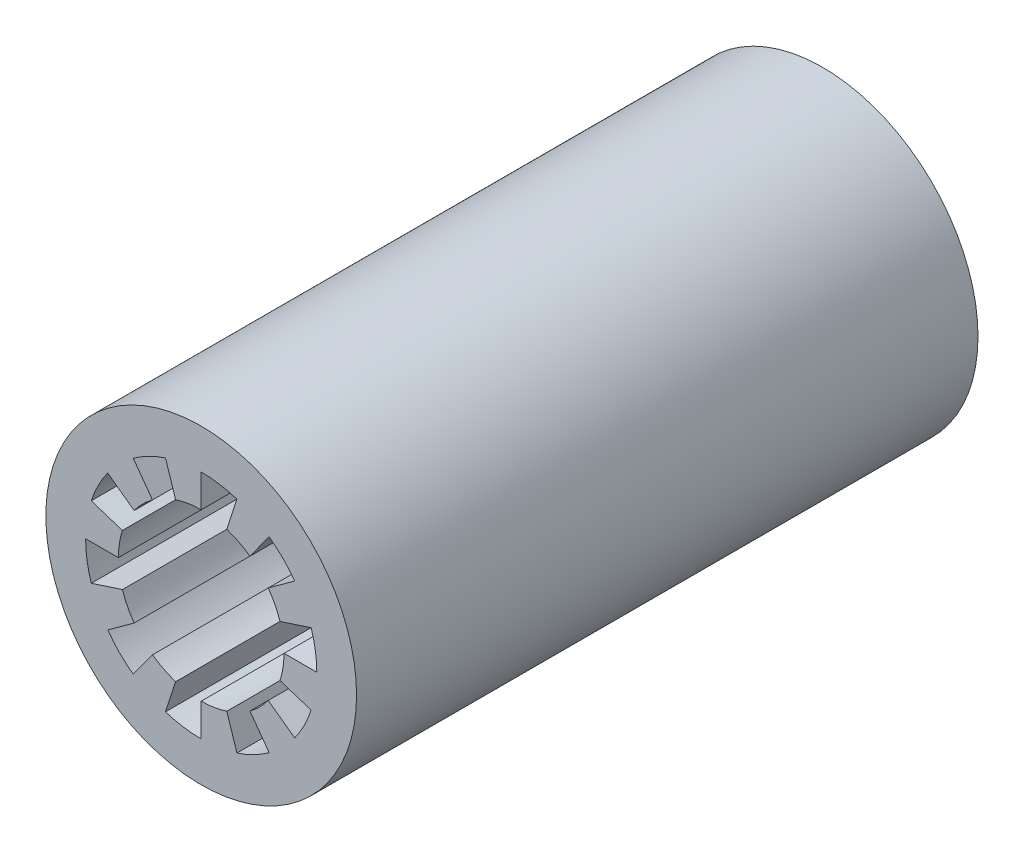
SolidWorks part; units mm, degrees
ref_plane "Front" through (0, 0, 0) normal (0, 0, 1) x (1, 0, 0)
ref_plane "Top" through (0, 0, 0) normal (0, 1, 0) x (1, 0, 0)
ref_plane "Right" through (0, 0, 0) normal (1, 0, 0) x (0, 0, -1)
sketch "Эскиз1" plane through (0, 0, 0) normal (0, 0, 1) x (1, 0, 0)
  line B0 (0, 5.58) -> (0, 4)
  line B1 (1.7243, 5.3069) -> (1.2361, 3.8042)
  line B2 (3.2798, 4.5143) -> (2.3511, 3.2361)
  line B3 (4.5143, 3.2798) -> (3.2361, 2.3511)
  line B4 (5.3069, 1.7243) -> (3.8042, 1.2361)
  line B5 (5.58, 0) -> (4, 0)
  line B6 (5.3069, -1.7243) -> (3.8042, -1.2361)
  line B7 (4.5143, -3.2798) -> (3.2361, -2.3511)
  line B8 (3.2798, -4.5143) -> (2.3511, -3.2361)
  line B9 (1.7243, -5.3069) -> (1.2361, -3.8042)
  line B10 (0, -5.58) -> (0, -4)
  line B11 (-1.7243, -5.3069) -> (-1.2361, -3.8042)
  line B12 (-3.2798, -4.5143) -> (-2.3511, -3.2361)
  line B13 (-4.5143, -3.2798) -> (-3.2361, -2.3511)
  line B14 (-5.3069, -1.7243) -> (-3.8042, -1.2361)
  line B15 (-5.58, 0) -> (-4, 0)
  line B16 (-5.3069, 1.7243) -> (-3.8042, 1.2361)
  line B17 (-4.5143, 3.2798) -> (-3.2361, 2.3511)
  line B18 (-3.2798, 4.5143) -> (-2.3511, 3.2361)
  line B19 (-1.7243, 5.3069) -> (-1.2361, 3.8042)
  arc B20 (0, 4) -> (-1.2361, 3.8042) centre (0, 0) ccw
  arc B21 (-4.5143, 3.2798) -> (-5.3069, 1.7243) centre (0, 0) ccw
  circle B22 centre (0, 0) radius 7.5
  arc B23 (2.3511, 3.2361) -> (1.2361, 3.8042) centre (0, 0) ccw
  arc B24 (3.8042, 1.2361) -> (3.2361, 2.3511) centre (0, 0) ccw
  arc B25 (3.8042, -1.2361) -> (4, 0) centre (0, 0) ccw
  arc B26 (2.3511, -3.2361) -> (3.2361, -2.3511) centre (0, 0) ccw
  arc B27 (0, -4) -> (1.2361, -3.8042) centre (0, 0) ccw
  arc B28 (-2.3511, -3.2361) -> (-1.2361, -3.8042) centre (0, 0) ccw
  arc B29 (-3.8042, -1.2361) -> (-3.2361, -2.3511) centre (0, 0) ccw
  arc B30 (-3.8042, 1.2361) -> (-4, 0) centre (0, 0) ccw
  arc B31 (-2.3511, 3.2361) -> (-3.2361, 2.3511) centre (0, 0) ccw
  arc B32 (-1.7243, 5.3069) -> (-3.2798, 4.5143) centre (0, 0) ccw
  arc B33 (1.7243, 5.3069) -> (0, 5.58) centre (0, 0) ccw
  arc B34 (4.5143, 3.2798) -> (3.2798, 4.5143) centre (0, 0) ccw
  arc B35 (5.58, 0) -> (5.3069, 1.7243) centre (0, 0) ccw
  arc B36 (4.5143, -3.2798) -> (5.3069, -1.7243) centre (0, 0) ccw
  arc B37 (1.7243, -5.3069) -> (3.2798, -4.5143) centre (0, 0) ccw
  arc B38 (-1.7243, -5.3069) -> (0, -5.58) centre (0, 0) ccw
  arc B39 (-4.5143, -3.2798) -> (-3.2798, -4.5143) centre (0, 0) ccw
  arc B40 (-5.58, 0) -> (-5.3069, -1.7243) centre (0, 0) ccw
sketch_block_instance "Блок1-1"
sketch_block "Блок1" parameters "D1"=5.6
extrude "Бобышка-Вытянуть1" add sketch "Эскиз1" along normal blind 30
